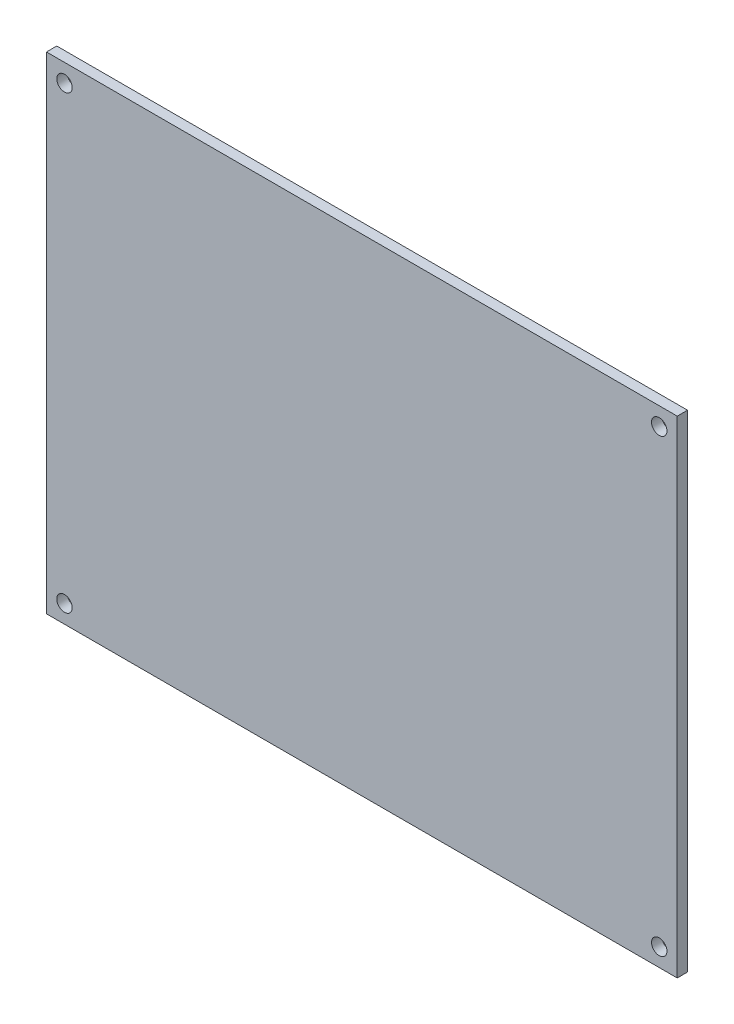
SolidWorks part; units mm, degrees
material "ABS"
ref_plane "Front Plane" through (0, 0, 0) normal (0, 0, 1) x (1, 0, 0)
ref_plane "Top Plane" through (0, 0, 0) normal (0, 1, 0) x (1, 0, 0)
ref_plane "Right Plane" through (0, 0, 0) normal (1, 0, 0) x (0, 0, -1)
sketch "Sketch2" plane through (0, 0, 0) normal (0, 0, 1) x (1, 0, 0)
  line L0 (-57.75, 43.75) -> (-57.75, 47.25) construction
  line L1 (-61.25, 47.25) -> (61.25, 47.25)
  line L2 (-61.25, 47.25) -> (-61.25, -47.25)
  line L3 (-61.25, -47.25) -> (61.25, -47.25)
  line L4 (61.25, 47.25) -> (61.25, -47.25)
  line L5 (-61.25, 47.25) -> (61.25, -47.25) construction
  line L6 (-61.25, -47.25) -> (61.25, 47.25) construction
  line L7 (-57.75, -43.75) -> (-57.75, -47.25) construction
  line L8 (57.75, 43.75) -> (61.25, 43.75) construction
  line L9 (-57.75, 43.75) -> (-61.25, 43.75) construction
  circle A0 centre (-57.75, 43.75) radius 1.5
  circle A1 centre (-57.75, -43.75) radius 1.5
  circle A2 centre (57.75, 43.75) radius 1.5
  circle A3 centre (57.75, -43.75) radius 1.5
  point P0 (0, 0)
  dimension "D3" = 3
  dimension "D1" = 94.5
  dimension "D2" = 122.5
  dimension "D4" = 115.5
  dimension "D5" = 87.5
extrude "Boss-Extrude1" add sketch "Sketch2" along normal blind 2
